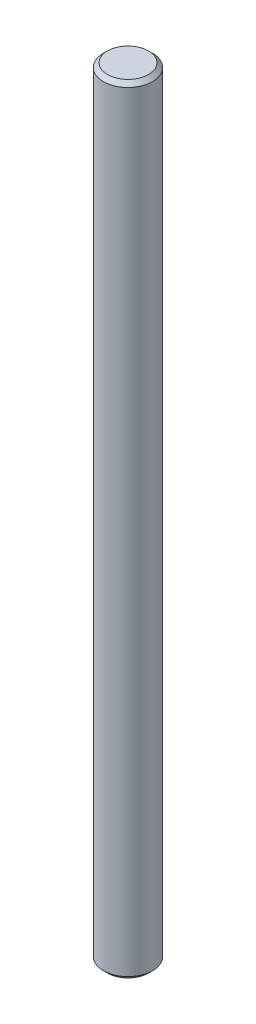
SolidWorks part; units mm, degrees
ref_plane "Front Plane" through (0, 0, 0) normal (0, 0, 1) x (1, 0, 0)
ref_plane "Top Plane" through (0, 0, 0) normal (0, 1, 0) x (1, 0, 0)
ref_plane "Right Plane" through (0, 0, 0) normal (1, 0, 0) x (0, 0, -1)
sketch "Sketch1" plane through (0, 0, 0) normal (0, 1, 0) x (1, 0, 0)
  circle A0 centre (0, 0) radius 3
  dimension "D1" = 6
extrude "Boss-Extrude1" add sketch "Sketch1" along normal blind 95
chamfer "Chamfer1" distance 0.5 angle 45 2 edges at (0, 0, 3) (0, 95, 3)
